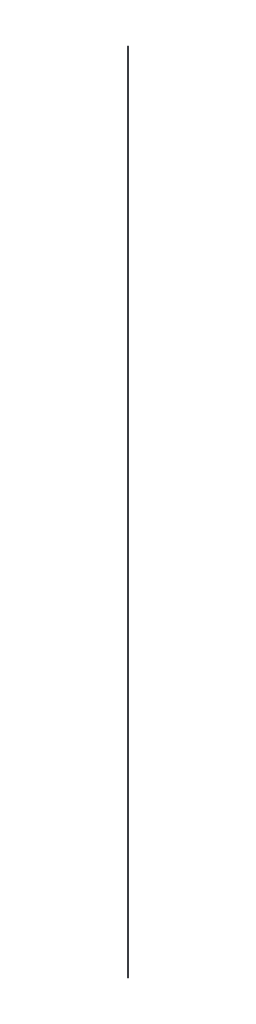
SolidWorks part; units mm, degrees
ref_plane "Front Plane" through (0, 0, 0) normal (0, 0, 1) x (1, 0, 0)
ref_plane "Top Plane" through (0, 0, 0) normal (0, 1, 0) x (1, 0, 0)
ref_plane "Right Plane" through (0, 0, 0) normal (1, 0, 0) x (0, 0, -1)
sketch "Sketch2" plane through (0, 0, 0) normal (0, 0, 1) x (1, 0, 0)
  line L0 (0, 0) -> (0, 765.2)
  dimension "D1" = 765.2
sketch "Sketch3" plane through (0, 0, 0) normal (0, 1, 0) x (1, 0, 0)
  circle A0 centre (0, 0) radius 0.25
  dimension "D1" = 0.5
sweep "Sweep1" add profiles "Sketch3" path "Sketch2"
